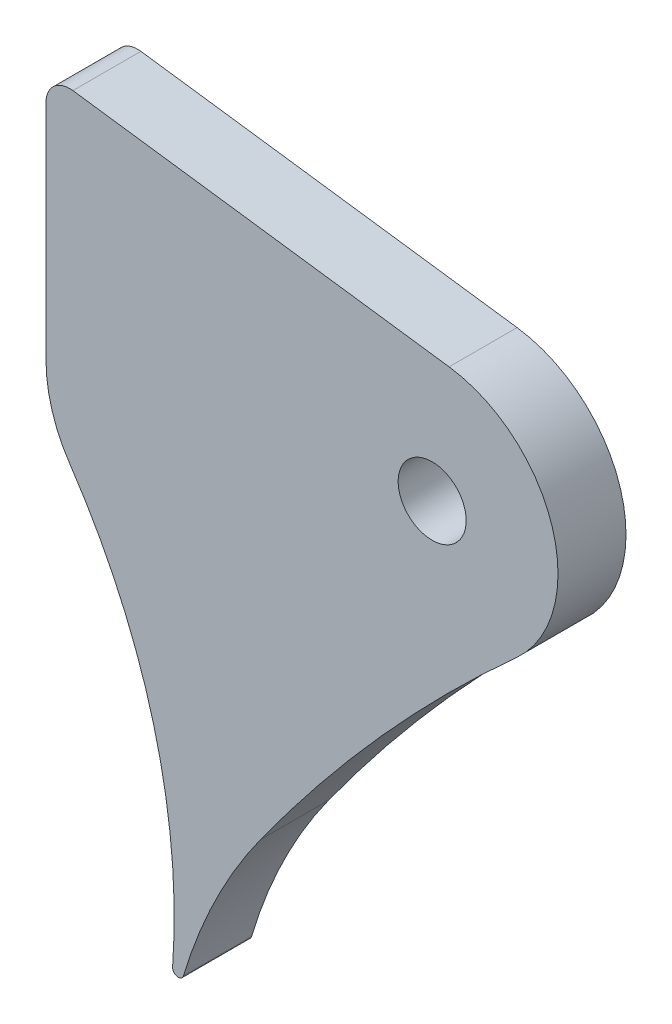
SolidWorks part; units mm, degrees
material "PPE"
ref_plane "Front Plane" through (0, 0, 0) normal (0, 0, 1) x (1, 0, 0)
ref_plane "Top Plane" through (0, 0, 0) normal (0, 1, 0) x (1, 0, 0)
ref_plane "Right Plane" through (0, 0, 0) normal (1, 0, 0) x (0, 0, -1)
sketch "Sketch1" plane through (0, 0, 0) normal (0, 0, 1) x (1, 0, 0)
  line L0 (38.5572, 99.3918) -> (167.8905, 99.3918) construction
  line L2 (0.5667, 10.6219) -> (4.8368, 10.0415)
  line L3 (0.5667, 10.6219) -> (-0.6962, 10.7936)
  line L4 (-1.0915, 10.4484) -> (-1.0915, 7.1625)
  arc A0 (4.8368, 10.0415) -> (5.8268, 6.8334) centre (4.5875, 8.2078) cw
  arc A1 (2.0622, 2.6331) -> (5.8268, 6.8334) centre (23.6216, -12.9025) cw
  arc A2 (2.0622, 2.6331) -> (0.9308, 0.3337) centre (8.3099, -1.869) ccw
  arc A3 (-0.6962, 10.7936) -> (-1.0915, 10.4484) centre (-0.7432, 10.4484) ccw
  arc A4 (-1.0915, 7.1625) -> (-0.7394, 6.0135) centre (0.9591, 7.1625) ccw
  arc A5 (-0.7394, 6.0135) -> (0.7706, 0.3631) centre (-8.1359, 1.01) cw
  arc A6 (0.7706, 0.3631) -> (0.9308, 0.3337) centre (0.8523, 0.3571) ccw
  point P12 (0, 0)
  point P17 (3.5741, 10.0509)
  point P18 (0, 0)
  point P22 (0, 0)
  point P23 (0, 0)
  point P25 (0, 0)
  point P26 (0.5667, 10.6219)
  point P27 (0, 0)
  point P28 (0.4913, 3.3154)
  point P29 (0, 0)
  point P30 (0, 0)
  dimension "D1" = 0.3571
  dimension "D2" = 0.0819
  dimension "D3" = 7.7008
  dimension "D4" = 26.5737
  dimension "D5" = 1.8506
  dimension "D8" = 0.3483
  dimension "D10" = 8.2078
  dimension "D11" = 2.0506
  dimension "D6" = 4.2701
  dimension "D7" = 1.2629
  dimension "D9" = 3.2859
  dimension "D12" = 7.1625
  dimension "D13" = 23.6216
  dimension "D14" = 0.8523
  dimension "D15" = 2.6981
  dimension "D16" = 2.6331
extrude "Boss-Extrude1" add sketch "Sketch1" along normal blind 1
sketch "Sketch2" plane through (0, 0, 1) normal (0, 0, 1) x (1, 0, 0)
  circle A0 centre (4.5875, 8.2078) radius 0.5
  dimension "D1" = 1
extrude "Cut-Extrude1" cut sketch "Sketch2" against normal blind 1
